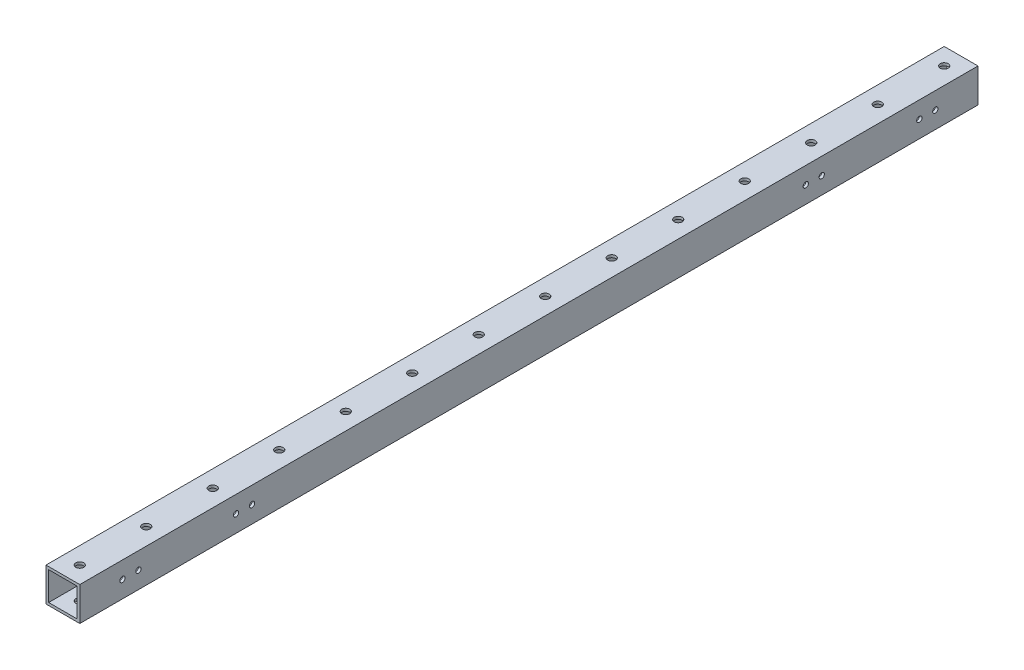
SolidWorks part; units mm, degrees
material "1060 Alloy"
ref_plane "Front Plane" through (0, 0, 0) normal (0, 0, 1) x (1, 0, 0)
ref_plane "Top Plane" through (0, 0, 0) normal (0, 1, 0) x (1, 0, 0)
ref_plane "Right Plane" through (0, 0, 0) normal (1, 0, 0) x (0, 0, -1)
sketch "Sketch1" plane through (0, 0, 0) normal (0, 0, 1) x (1, 0, 0)
  line L0 (-10.7, -10.7) -> (-10.7, 10.7)
  line L1 (12.7, -12.7) -> (-12.7, -12.7)
  line L2 (12.7, -12.7) -> (12.7, 12.7)
  line L3 (12.7, 12.7) -> (-12.7, 12.7)
  line L4 (-12.7, -12.7) -> (-12.7, 12.7)
  line L5 (12.7, -12.7) -> (-12.7, 12.7) construction
  line L6 (12.7, 12.7) -> (-12.7, -12.7) construction
  line L7 (10.7, 10.7) -> (-10.7, 10.7)
  line L8 (10.7, -10.7) -> (10.7, 10.7)
  line L9 (10.7, -10.7) -> (-10.7, -10.7)
  point P0 (0, 0)
  dimension "D1" = 2
extrude "Boss-Extrude1" add sketch "Sketch1" along normal blind 675.4
sketch "Sketch3" plane through (0, 12.7, 0) normal (0, 1, 0) x (1, 0, 0)
  circle A1 centre (0, -662.7) radius 3
  circle A2 centre (0, -612.7) radius 3
  circle A3 centre (0, -562.7) radius 3
  circle A4 centre (0, -512.7) radius 3
  circle A5 centre (0, -462.7) radius 3
  circle A6 centre (0, -412.7) radius 3
  circle A7 centre (0, -362.7) radius 3
  circle A8 centre (0, -312.7) radius 3
  circle A9 centre (0, -262.7) radius 3
  circle A10 centre (0, -212.7) radius 3
  circle A11 centre (0, -162.7) radius 3
  circle A12 centre (0, -112.7) radius 3
  circle A13 centre (0, -62.7) radius 3
  circle A14 centre (0, -12.7) radius 3
  dimension "D1" = 14
extrude "Cut-Extrude1" cut sketch "Sketch3" against normal blind 650
sketch "Sketch4" plane through (12.7, 0, 0) normal (1, 0, 0) x (0, 0, -1)
  circle A3 centre (-44.1, 0) radius 2
  circle A4 centre (-32.1, 0) radius 2
  circle A8 centre (-117.5, 0) radius 2
  circle A9 centre (-129.5, 0) radius 2
  circle A10 centre (-643.3, 0) radius 2
  circle A11 centre (-631.3, 0) radius 2
  circle A12 centre (-557.9, 0) radius 2
  circle A13 centre (-545.9, 0) radius 2
extrude "Cut-Extrude2" cut sketch "Sketch4" against normal through all both and the other way through all
